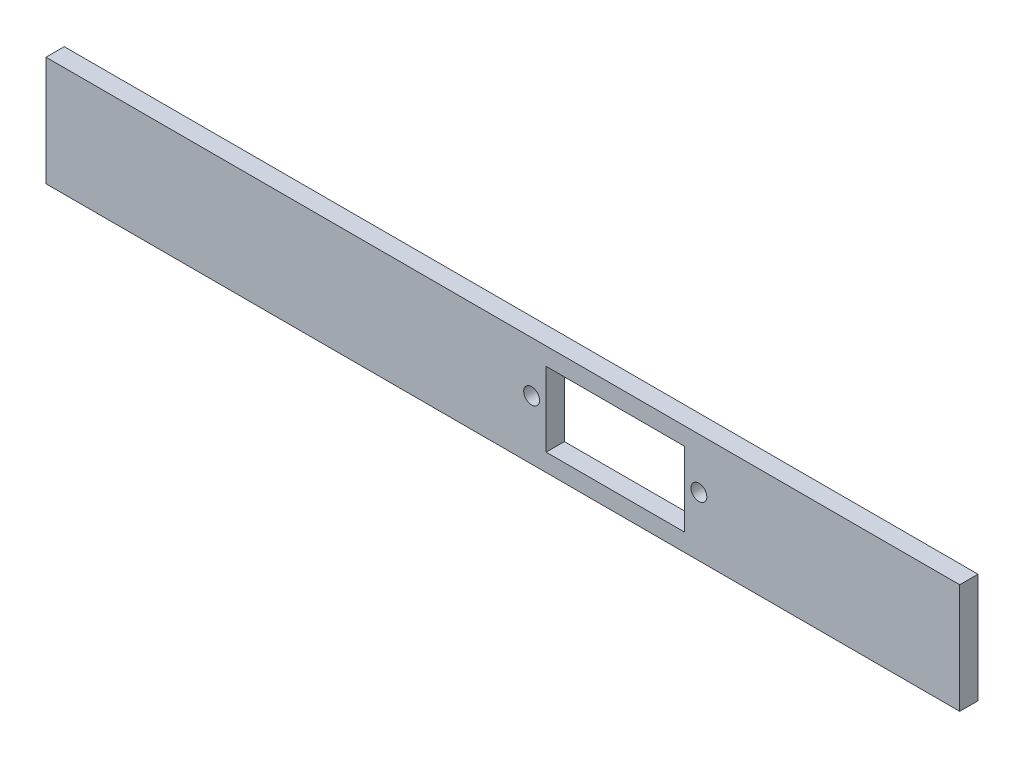
SolidWorks part; units mm, degrees
ref_plane "Front Plane" through (0, 0, 0) normal (0, 0, 1) x (1, 0, 0)
ref_plane "Top Plane" through (0, 0, 0) normal (0, 1, 0) x (1, 0, 0)
ref_plane "Right Plane" through (0, 0, 0) normal (1, 0, 0) x (0, 0, -1)
sketch "Sketch1" plane through (0, 0, 0) normal (0, 0, 1) x (1, 0, 0)
  line L1 (-75, 9) -> (75, 9)
  line L2 (-75, 9) -> (-75, -9)
  line L3 (-75, -9) -> (75, -9)
  line L4 (75, 9) -> (75, -9)
  line L5 (-75, 9) -> (75, -9) construction
  line L6 (-75, -9) -> (75, 9) construction
  point P0 (0, 0)
  dimension "D1" = 150
  dimension "D2" = 18
extrude "Boss-Extrude1" add sketch "Sketch1" along normal blind 3
sketch "Sketch2" plane through (0, 0, 0) normal (0, 0, -1) x (-1, 0, 0)
  line L0 (-75, -9) -> (-75, 9) construction
  line L1 (-29.8, 6.1) -> (-7.1, 6.1)
  line L2 (-29.8, 6.1) -> (-29.8, -6.1)
  line L3 (-29.8, -6.1) -> (-7.1, -6.1)
  line L4 (-7.1, 6.1) -> (-7.1, -6.1)
  line L6 (-75, 0) -> (75, 0) construction
  line L7 (75, 9) -> (75, -9) construction
  dimension "D1" = 22.7
  dimension "D2" = 12.2
  dimension "D3" = 45.2
extrude "Cut-Extrude1" cut sketch "Sketch2" against normal blind 3
sketch "Sketch3" plane through (0, 0, 3) normal (0, 0, 1) x (1, 0, 0)
  circle A0 centre (32.175, 0.1) radius 1.2
extrude "Boss-Extrude2" add sketch "Sketch3" against normal blind 3
sketch "Sketch4" plane through (0, 0, 0) normal (0, 0, -1) x (-1, 0, 0)
  line L3 (-18.45, 6.1) -> (-18.45, -6.1) construction
  line L4 (-7.1, 6.1) -> (-29.8, 6.1) construction
  line L5 (-29.8, -6.1) -> (-7.1, -6.1) construction
  line L6 (-29.8, 6.1) -> (-29.8, -6.1) construction
  circle A0 centre (-32.18, 0.7232) radius 1.3
  circle A1 centre (-4.72, 0.7232) radius 1.3
  dimension "D1" = 2.6
  dimension "D2" = 2.38
extrude "Cut-Extrude2" cut sketch "Sketch4" against normal blind 3
